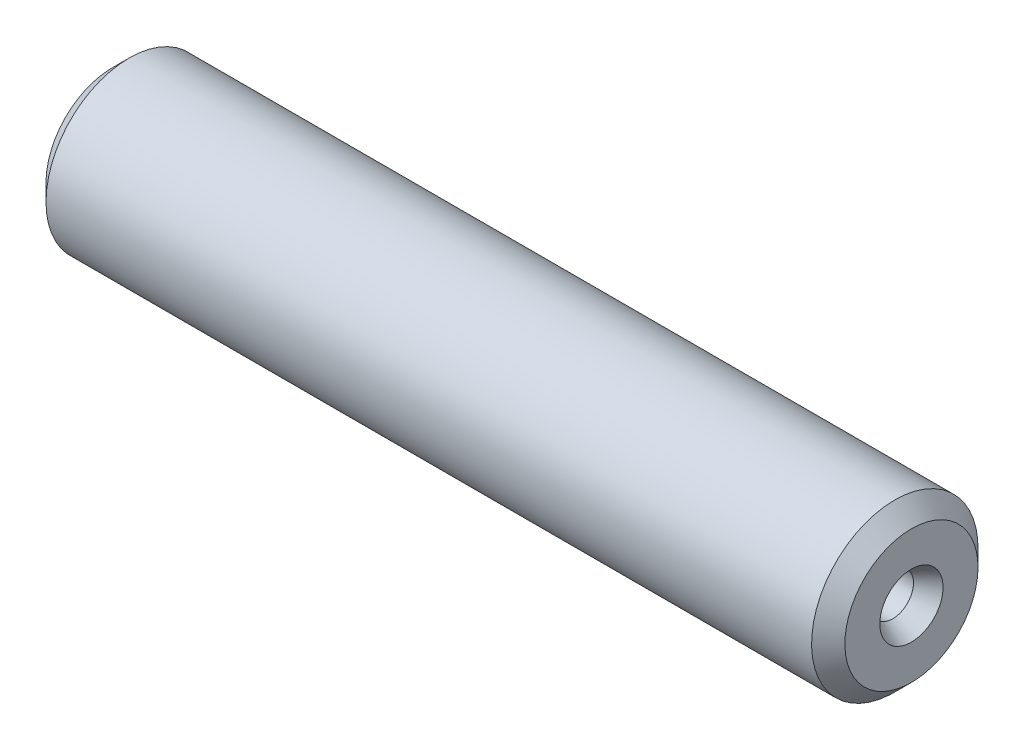
SolidWorks part; units mm, degrees
material "4140 H/T"
ref_plane "Front Plane" through (0, 0, 0) normal (0, 0, 1) x (1, 0, 0)
ref_plane "Top Plane" through (0, 0, 0) normal (0, 1, 0) x (1, 0, 0)
ref_plane "Right Plane" through (0, 0, 0) normal (1, 0, 0) x (0, 0, -1)
sketch "Sketch1" plane through (0, 0, 0) normal (0, 0, 1) x (1, 0, 0)
  line L0 (0, 1.9) -> (0, 5)
  line L1 (0, 5) -> (-48, 5)
  line L2 (-48, 5) -> (-48, 0)
  line L3 (0, 0) -> (-48, 0) construction
  line L4 (-4, 0) -> (-48, 0)
  line L5 (0, 1.9) -> (-1.1258, 1.25)
  line L6 (-1.1258, 1.25) -> (-3.2489, 1.25)
  line L7 (-3.2489, 1.25) -> (-4, 0)
  line L8 (-1.1258, 1.25) -> (-3.2909, 0) construction
  dimension "D1" = 48
  dimension "D2" = 10
  dimension "D3" = 59
  dimension "D4" = 2.5
  dimension "D5" = 30
  dimension "D6" = 3.8
  dimension "D7" = 4
revolve "Revolve1" add sketch "Sketch1" angle 360 about L3
cosmetic thread "Cosmetic Thread1" parameters "D1"=26, "D2"=8.17
cosmetic thread "Cosmetic Thread2" parameters "D1"=16, "D2"=8.17
chamfer "Chamfer1" distance 1 angle 45 2 edges at (-48, 5, 0) (0, 5, 0)
